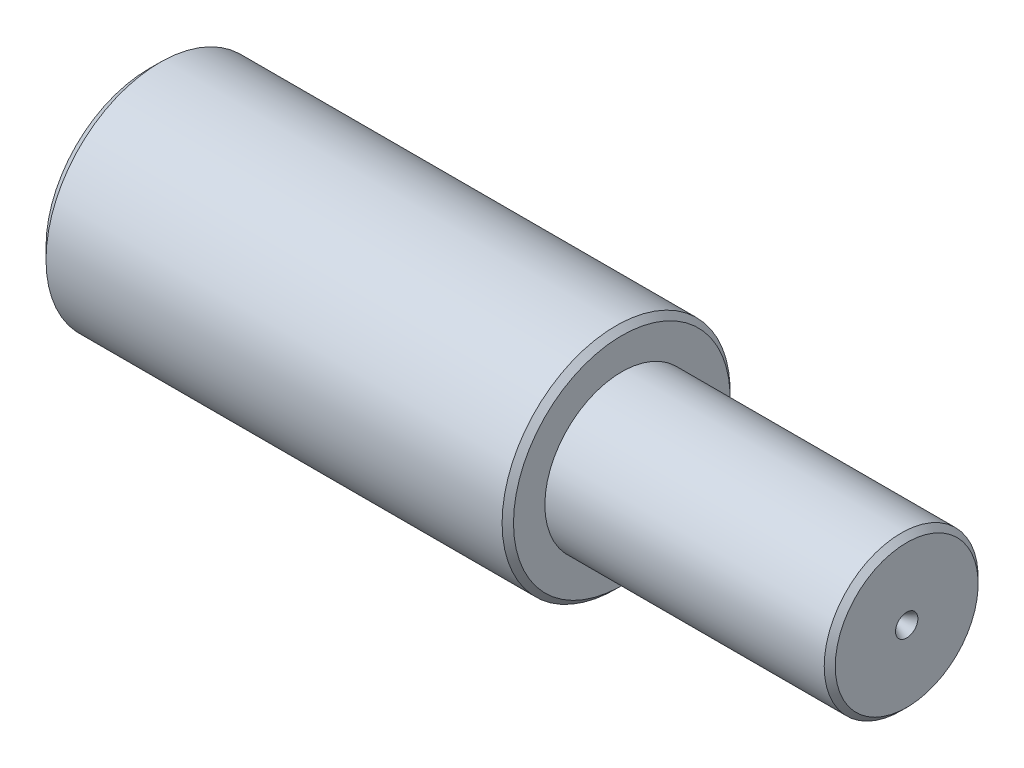
SolidWorks part; units mm, degrees
ref_plane "Спереди" through (0, 0, 0) normal (0, 0, 1) x (1, 0, 0)
ref_plane "Сверху" through (0, 0, 0) normal (0, 1, 0) x (1, 0, 0)
ref_plane "Справа" through (0, 0, 0) normal (1, 0, 0) x (0, 0, -1)
sketch "Эскиз2" plane through (0, 0, 0) normal (0, 1, 0) x (1, 0, 0)
  line L0 (-45.5275, 22.3375) -> (34.4725, 22.3375)
  line L1 (35.4725, 21.3375) -> (35.4725, 15.8375)
  line L2 (35.4725, 15.8375) -> (84.4725, 15.8375)
  line L3 (-47.5275, 20.3375) -> (-47.5275, 2.3375)
  line L4 (85.4416, 14.8685) -> (85.4416, 4.2964)
  line L5 (-47.5275, 2.3375) -> (82.2592, 2.3375)
  line L6 (34.4725, 22.3375) -> (35.4725, 21.3375)
  line L7 (-58.608, 2.3375) -> (159.8552, 2.3375) construction
  line L8 (84.4725, 15.8375) -> (85.4416, 14.8685)
  line L9 (-45.5275, 22.3375) -> (-47.5275, 20.3375)
  line L10 (82.2592, 2.3375) -> (85.4416, 4.2964)
  point P1 (35.4725, 22.3375)
  point P4 (85.4725, 15.8375)
  point P10 (-47.5275, 22.3375)
  point P11 (0, 0)
  dimension "D1" = 20
  dimension "D2" = 13.5
  dimension "D3" = 2
  dimension "D4" = 45
revolve "Повернуть1" add sketch "Эскиз2" angle 360 about L7
